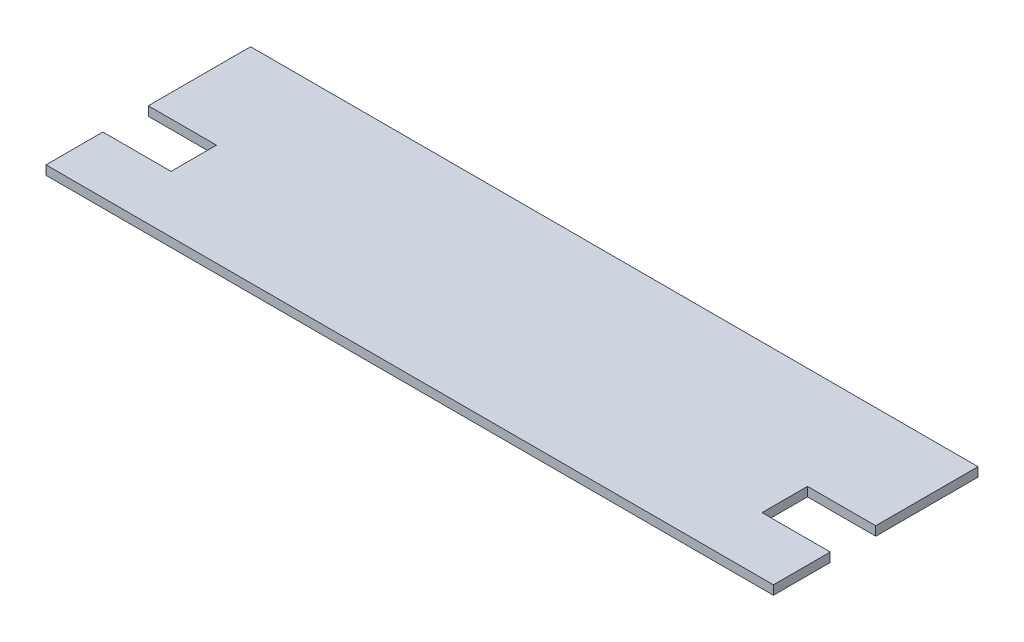
SolidWorks part; units mm, degrees
ref_plane "前视基准面" through (0, 0, 0) normal (0, 0, 1) x (1, 0, 0)
ref_plane "上视基准面" through (0, 0, 0) normal (0, 1, 0) x (1, 0, 0)
ref_plane "右视基准面" through (0, 0, 0) normal (1, 0, 0) x (0, 0, -1)
sketch "草图1" plane through (0, 0, 0) normal (0, 1, 0) x (1, 0, 0)
  line L1 (0, 0) -> (320, 0)
  line L2 (0, 0) -> (0, 90)
  line L3 (0, 90) -> (320, 90)
  line L4 (320, 0) -> (320, 90)
  dimension "D1" = 320
  dimension "D2" = 90
extrude "凸台-拉伸1" add sketch "草图1" along normal blind 4
sketch "草图2" plane through (0, 4, 0) normal (0, 1, 0) x (1, 0, 0)
  line L0 (160, 90) -> (160, 0) construction
  line L1 (320, 90) -> (0, 90) construction
  line L2 (0, 45) -> (30, 45)
  line L3 (15, 35) -> (305, 35) construction
  line L6 (0, 45) -> (0, 25)
  line L15 (0, 25) -> (30, 25)
  line L22 (0, 0) -> (320, 0) construction
  line L27 (30, 45) -> (30, 25)
  line L28 (0, 45) -> (30, 25) construction
  line L29 (0, 25) -> (30, 45) construction
  line L30 (320, 45) -> (290, 45)
  line L31 (320, 45) -> (320, 25)
  line L32 (320, 25) -> (290, 25)
  line L33 (290, 45) -> (290, 25)
  line L34 (320, 45) -> (290, 25) construction
  line L35 (320, 25) -> (290, 45) construction
  line L36 (0, 90) -> (0, 0) construction
  line L37 (320, 0) -> (320, 90) construction
  dimension "D1" = 20
  dimension "D3" = 35
  dimension "D2" = 260
extrude "切除-拉伸1" cut sketch "草图2" against normal through all
